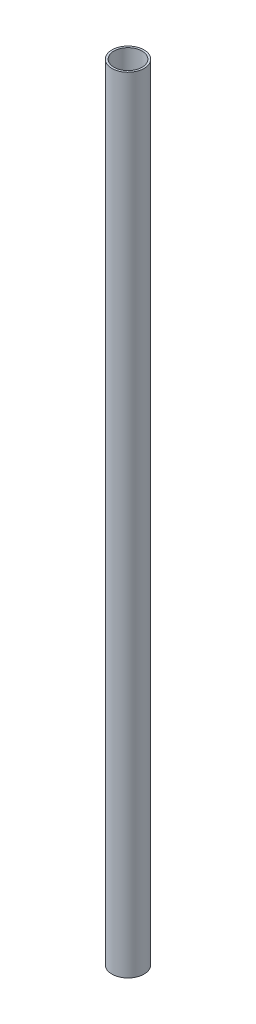
SolidWorks part; units mm, degrees
ref_plane "Front Plane" through (0, 0, 0) normal (0, 0, 1) x (1, 0, 0)
ref_plane "Top Plane" through (0, 0, 0) normal (0, 1, 0) x (1, 0, 0)
ref_plane "Right Plane" through (0, 0, 0) normal (1, 0, 0) x (0, 0, -1)
sketch "Sketch1" plane through (0, 0, 0) normal (0, 1, 0) x (1, 0, 0)
  circle A0 centre (0, 0) radius 3.5
  circle A1 centre (0, 0) radius 4
  dimension "D1" = 8
  dimension "D2" = 0.5
extrude "Boss-Extrude1" add sketch "Sketch1" along normal blind 195
